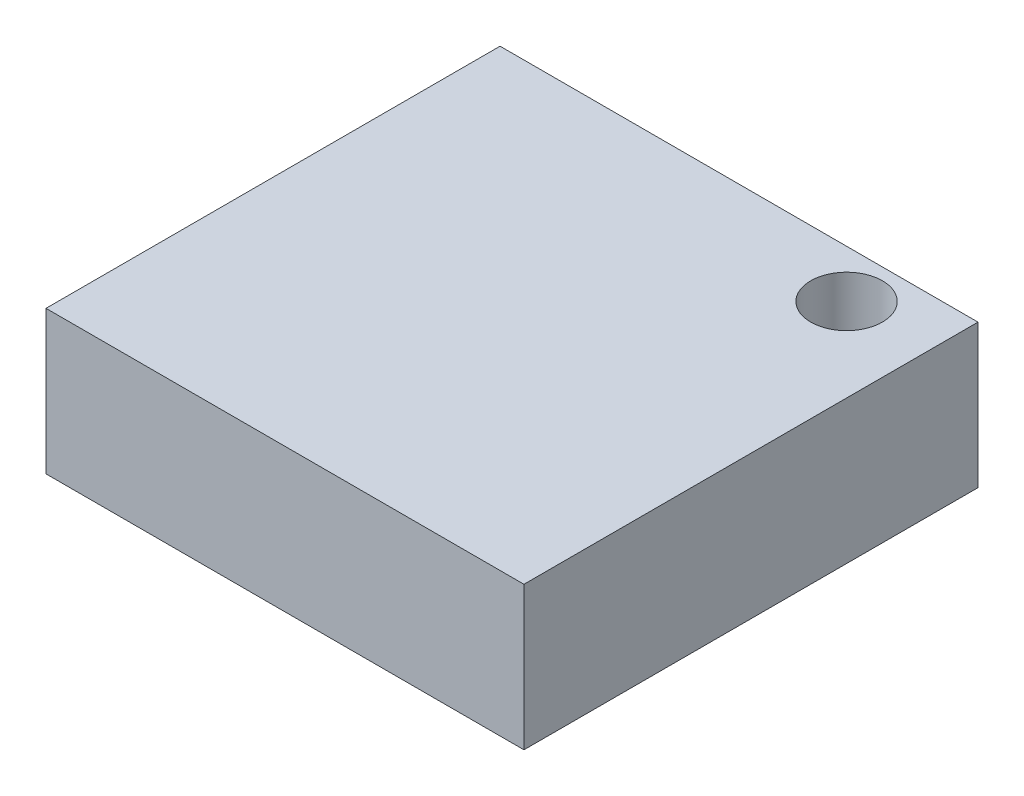
SolidWorks part; units mm, degrees
ref_plane "Plan de face" through (0, 0, 0) normal (0, 0, 1) x (1, 0, 0)
ref_plane "Plan de dessus" through (0, 0, 0) normal (0, 1, 0) x (1, 0, 0)
ref_plane "Plan de droite" through (0, 0, 0) normal (1, 0, 0) x (0, 0, -1)
sketch "Esquisse1" plane through (0, 0, 0) normal (0, 1, 0) x (1, 0, 0)
  line L1 (0, 0) -> (20, 0)
  line L2 (0, 0) -> (0, 19)
  line L3 (0, 19) -> (20, 19)
  line L4 (20, 0) -> (20, 19)
  dimension "D1" = 20
  dimension "D2" = 19
extrude "Boss.-Extru.1" add sketch "Esquisse1" along normal blind 6
sketch "Esquisse2" plane through (0, 6, 0) normal (0, 1, 0) x (1, 0, 0)
  line L0 (20, 19) -> (0, 19) construction
  line L1 (20, 0) -> (20, 19) construction
  circle A0 centre (16.5, 17) radius 1.5
  dimension "D1" = 3
  dimension "D2" = 2
  dimension "D3" = 3.5
extrude "Enlèv. mat.-Extru.1" cut sketch "Esquisse2" against normal blind 6
